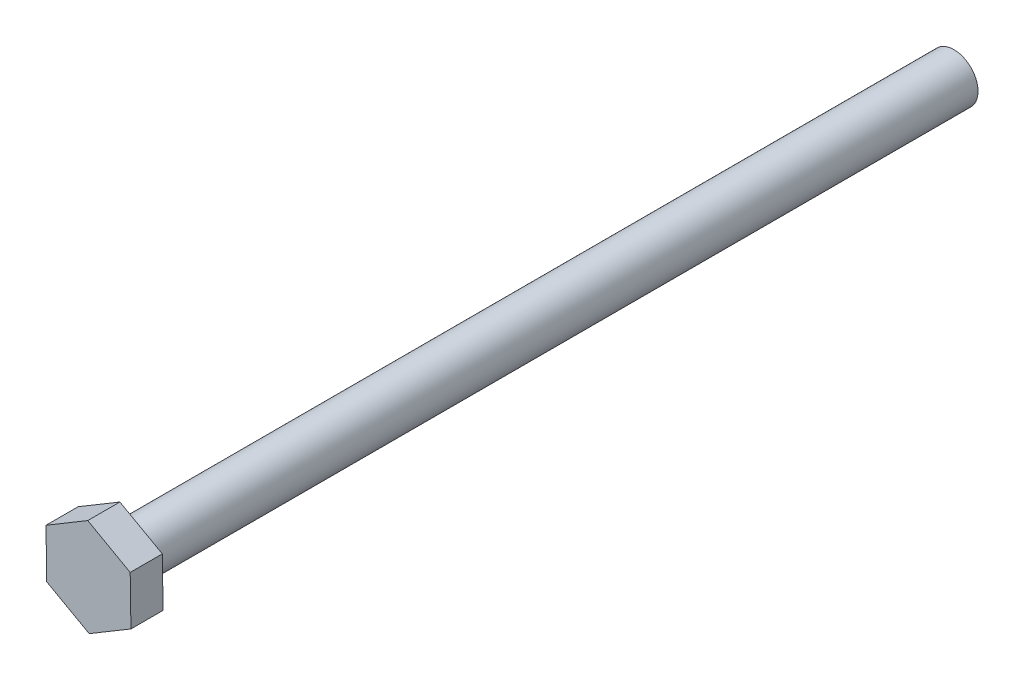
SolidWorks part; units mm, degrees
ref_plane "Front Plane" through (0, 0, 0) normal (0, 0, 1) x (1, 0, 0)
ref_plane "Top Plane" through (0, 0, 0) normal (0, 1, 0) x (1, 0, 0)
ref_plane "Right Plane" through (0, 0, 0) normal (1, 0, 0) x (0, 0, -1)
sketch "Sketch1" plane through (0, 0, 0) normal (0, 0, 1) x (1, 0, 0)
  line L1 (5.5078, 3.2904) -> (-0.0956, 6.4151)
  line L2 (-0.0956, 6.4151) -> (-5.6035, 3.1247)
  line L3 (-5.6035, 3.1247) -> (-5.5078, -3.2904)
  line L4 (-5.5078, -3.2904) -> (0.0956, -6.4151)
  line L5 (0.0956, -6.4151) -> (5.6035, -3.1247)
  line L6 (5.6035, -3.1247) -> (5.5078, 3.2904)
  circle A0 centre (0, 0) radius 5.5562 construction
  dimension "D1" = 11.1125
extrude "Boss-Extrude1" add sketch "Sketch1" along normal blind 4.2418 contours L1 L2 L3 L4 L5 L6
sketch "Sketch2" plane through (0, 0, 0) normal (0, 0, -1) x (-1, 0, 0)
  circle A0 centre (0, 0) radius 3.175
  dimension "D1" = 6.35
extrude "Boss-Extrude2" add sketch "Sketch2" along normal blind 109.982
